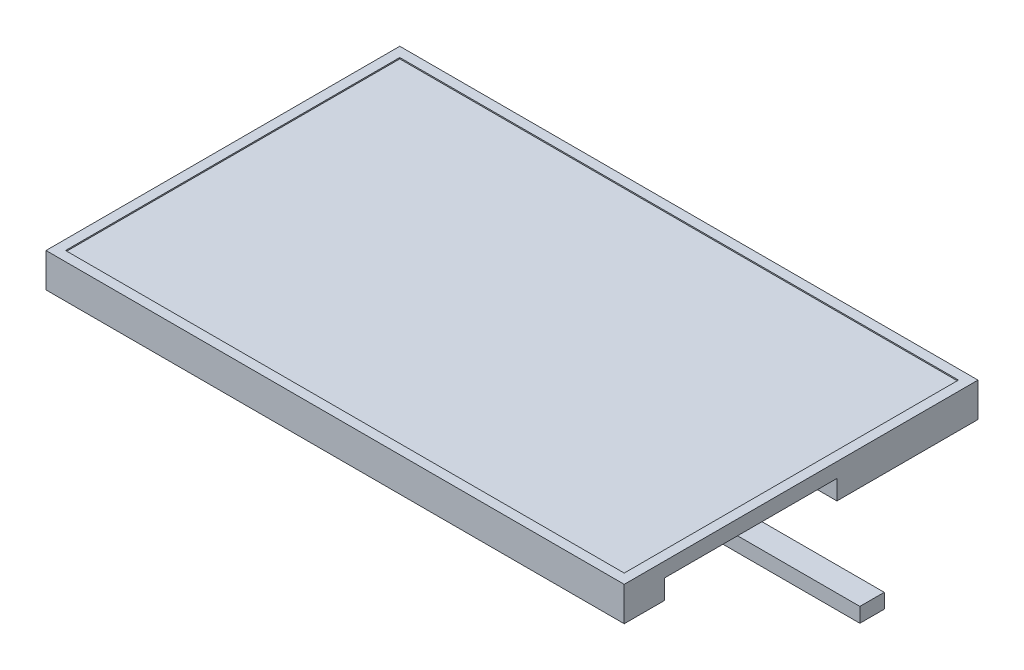
SolidWorks part; units mm, degrees
ref_plane "前视基准面" through (0, 0, 0) normal (0, 0, 1) x (1, 0, 0)
ref_plane "上视基准面" through (0, 0, 0) normal (0, 1, 0) x (1, 0, 0)
ref_plane "右视基准面" through (0, 0, 0) normal (1, 0, 0) x (0, 0, -1)
other "Configuration Table"
sketch "草图1" plane through (0, 0, 0) normal (0, 1, 0) x (1, 0, 0)
  line L1 (-118.5, 145) -> (118.5, 145)
  line L2 (-118.5, 145) -> (-118.5, 0)
  line L3 (-118.5, 0) -> (118.5, 0)
  line L4 (118.5, 145) -> (118.5, 0)
  point P4 (0, 0)
  dimension "D1" = 237
  dimension "D2" = 145
extrude "凸台-拉伸1" add sketch "草图1" along normal blind 14
sketch "草图2" plane through (0, 0, 0) normal (0, -1, 0) x (1, 0, 0)
  line L0 (-118.5, 0) -> (118.5, 0) construction
  line L1 (118.5, 0) -> (118.5, -145) construction
  circle A0 centre (37.5, -110) radius 2
  circle A1 centre (-37.5, -110) radius 2
  circle A2 centre (-37.5, -35) radius 2
  circle A3 centre (37.5, -35) radius 2
  circle A4 centre (0, -24) radius 3
  dimension "D1" = 35
  dimension "D2" = 75
  dimension "D3" = 75
  dimension "D4" = 81
  dimension "D5" = 4
  dimension "D6" = 6
  dimension "D7" = 24
extrude "切除-拉伸1" cut sketch "草图2" against normal blind 4
sketch "草图3" plane through (0, 0, 0) normal (0, -1, 0) x (1, 0, 0)
  line L0 (118.5, 0) -> (118.5, -145) construction
  line L1 (118.5, -87.1819) -> (86.6233, -87.1819)
  line L2 (118.5, -87.1819) -> (118.5, -16.511)
  line L3 (118.5, -16.511) -> (86.6233, -16.511)
  line L4 (86.6233, -87.1819) -> (86.6233, -16.511)
extrude "切除-拉伸2" cut sketch "草图3" against normal blind 8
sketch "草图4" plane through (0, 14, 0) normal (0, 1, 0) x (1, 0, 0)
  line L12 (-114.5, 141) -> (-114.5, 4)
  line L13 (-114.5, 4) -> (114.5, 4)
  line L14 (114.5, 4) -> (114.5, 141)
  line L15 (114.5, 141) -> (-114.5, 141)
  line L16 (-114.5, 141) -> (-114.5, 4)
  line L17 (-114.5, 4) -> (114.5, 4)
  line L18 (114.5, 4) -> (114.5, 141)
  line L19 (114.5, 141) -> (-114.5, 141)
  dimension "D1" = 4
extrude "切除-拉伸3" cut sketch "草图4" against normal blind 0.5
sketch "草图5" plane through (86.6233, 0, 0) normal (1, 0, 0) x (0, 0, -1)
  line L0 (16.511, 0) -> (87.1819, 0) construction
  line L1 (48.4583, 6) -> (58.4583, 6)
  line L2 (48.4583, 6) -> (48.4583, 0)
  line L3 (48.4583, 0) -> (58.4583, 0)
  line L4 (58.4583, 6) -> (58.4583, 0)
  dimension "D1" = 10
  dimension "D2" = 6
extrude "凸台-拉伸2" add sketch "草图5" along normal blind 80
